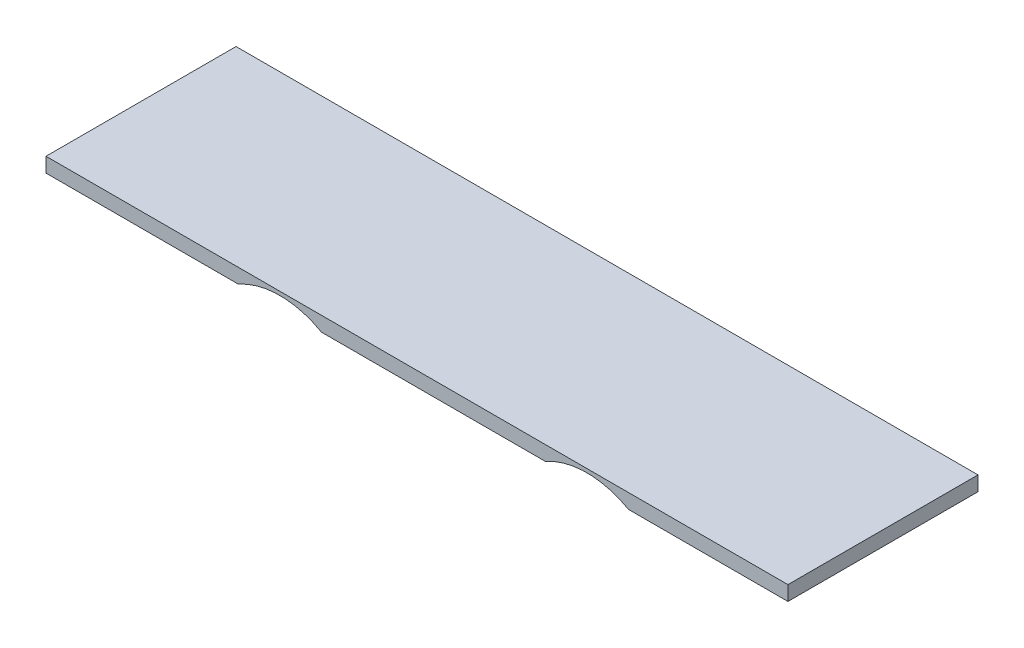
SolidWorks part; units mm, degrees
ref_plane "Front Plane" through (0, 0, 0) normal (0, 0, 1) x (1, 0, 0)
ref_plane "Top Plane" through (0, 0, 0) normal (0, 1, 0) x (1, 0, 0)
ref_plane "Right Plane" through (0, 0, 0) normal (1, 0, 0) x (0, 0, -1)
sketch "Sketch1" plane through (0, 0, 0) normal (0, 0, 1) x (1, 0, 0)
  line L0 (0, 0) -> (101.5, 0)
  line L1 (0, 0) -> (0, -2)
  line L2 (0, -2) -> (26.3211, -2)
  line L3 (101.5, -2) -> (101.5, 0)
  line L4 (37.6789, -2) -> (68.3211, -2)
  line L5 (79.6789, -2) -> (101.5, -2)
  arc A0 (37.6789, -2) -> (26.3211, -2) centre (32, -12) ccw
  arc A1 (79.6789, -2) -> (68.3211, -2) centre (74, -12) ccw
  dimension "D3" = 23
  dimension "D4" = 42
  dimension "D1" = 2
  dimension "D2" = 101.5
  dimension "D5" = 32
  dimension "D6" = 10
extrude "Boss-Extrude1" add sketch "Sketch1" along normal blind 26
